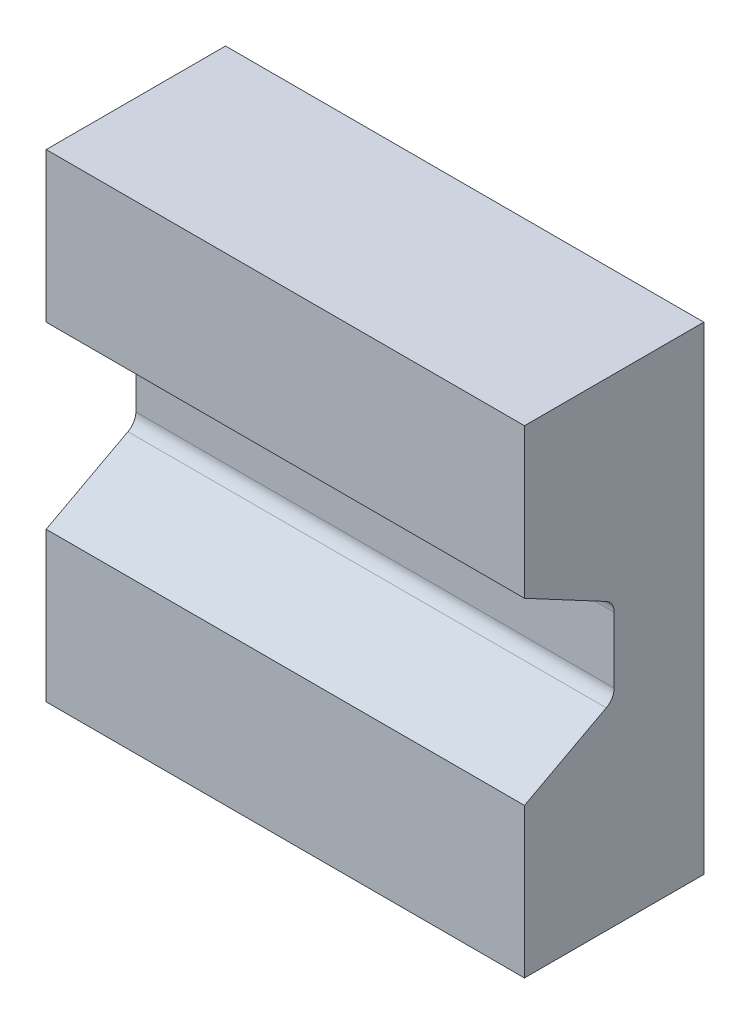
SolidWorks part; units mm, degrees
ref_plane "Alzado" through (0, 0, 0) normal (0, 0, 1) x (1, 0, 0)
ref_plane "Planta" through (0, 0, 0) normal (0, 1, 0) x (1, 0, 0)
ref_plane "Vista lateral" through (0, 0, 0) normal (1, 0, 0) x (0, 0, -1)
sketch "Croquis1" plane through (0, 0, 0) normal (0, 0, 1) x (1, 0, 0)
  line L0 (40, 40) -> (-40, -40) construction
  line L1 (-40, 40) -> (40, 40)
  line L2 (-40, 40) -> (-40, -40)
  line L3 (-40, -40) -> (40, -40)
  line L4 (40, 40) -> (40, -40)
  dimension "D1" = 80
  dimension "D2" = 80
extrude "Saliente-Extruir1" add sketch "Croquis1" along normal blind 30
sketch "Croquis2" plane through (40, 0, 0) normal (1, 0, 0) x (0, 0, -1)
  line L0 (0, 0) -> (-30, 0) construction
  line L1 (-30, -40) -> (-30, 40) construction
  line L2 (-30, 15) -> (-16.3235, 7.7059)
  line L3 (-15, 5.5) -> (-15, -5.5)
  line L4 (-30, 15) -> (-30, -15)
  line L5 (-30, -15) -> (-16.3235, -7.7059)
  arc A0 (-15, 5.5) -> (-16.3235, 7.7059) centre (-17.5, 5.5) ccw
  arc A1 (-15, -5.5) -> (-16.3235, -7.7059) centre (-17.5, -5.5) cw
  point P9 (-15, 0)
  dimension "D4" = 5
  dimension "D1" = 15
  dimension "D3" = 15
extrude "Cortar-Extruir1" cut sketch "Croquis2" against normal through all
